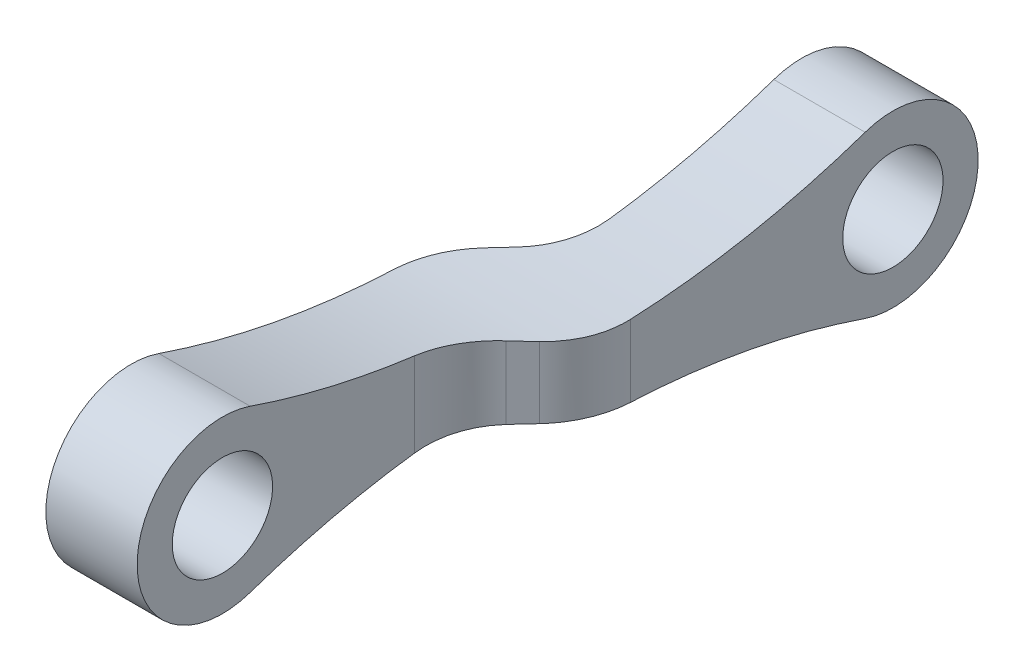
SolidWorks part; units mm, degrees
ref_plane "Front Plane" through (0, 0, 0) normal (0, 0, 1) x (1, 0, 0)
ref_plane "Top Plane" through (0, 0, 0) normal (0, 1, 0) x (1, 0, 0)
ref_plane "Right Plane" through (0, 0, 0) normal (1, 0, 0) x (0, 0, -1)
sketch "Sketch1" plane through (0, 0, 0) normal (1, 0, 0) x (0, 0, -1)
  line L0 (0, 0) -> (-36.65, 0) construction
  line L1 (-39.15, 0) -> (-42.72, 0) construction
  circle A0 centre (0, 0) radius 3.57
  arc A1 (-1.9739, -5.7401) -> (-1.9739, 5.7401) centre (0, 0) ccw
  circle A2 centre (-42.72, 0) radius 3.57
  arc A3 (-40.7461, 5.7401) -> (-40.7461, -5.7401) centre (-42.72, 0) ccw
  arc A4 (-40.7461, 5.7401) -> (-1.9739, 5.7401) centre (-21.36, 62.1155) ccw
  arc A5 (-40.7461, -5.7401) -> (-1.9739, -5.7401) centre (-21.36, -62.1155) cw
  point P13 (-21.36, -2.5)
  dimension "D1" = 7.14
  dimension "D2" = 2.5
  dimension "D4" = 7.14
  dimension "D5" = 2.5
  dimension "D3" = 42.72
  dimension "D6" = 2.5
extrude "Boss-Extrude1" add sketch "Sketch1" along normal blind 11.5
sketch "Sketch2" plane through (0, 0, 0) normal (0, 1, 0) x (1, 0, 0)
  line L0 (5, -48.79) -> (5, -21.3009) construction
  line L1 (0, -48.79) -> (11.5, -48.79) construction
  line L2 (0, -1.9739) -> (0, -40.7461) construction
  line L3 (6.5, -48.79) -> (6.5, -26.36) construction
  line L4 (11.5, 6.07) -> (0, 6.07) construction
  line L5 (11.5, -40.7461) -> (11.5, -1.9739) construction
  line L6 (5, -21.3266) -> (6.5, -21.3343) construction
  line L8 (11.5, -48.79) -> (6.5, -48.79)
  line L9 (11.5, -48.79) -> (11.5, -21.36)
  line L11 (6.5, -48.79) -> (6.5, -26.36)
  line L14 (5, -16.3009) -> (5, 6.07)
  line L15 (5, 6.07) -> (0, 6.07)
  line L16 (0, -21.3009) -> (0, 6.07)
  line L17 (11.5, -21.36) -> (6.5, -26.36)
  line L18 (0, -21.3009) -> (5, -16.3009)
  line L19 (6.5, -21.36) -> (6.5, 6.07) construction
  line L20 (5, -16.3009) -> (5, 6.1882) construction
  dimension "D1" = 5
  dimension "D2" = 5
extrude "Cut-Extrude2" cut sketch "Sketch2" against normal through all and the other way through all
fillet "Fillet1" radius 6.5 4 edges at (0, 0, 21.3009) (5, 0, 16.3009) (6.5, 0, 26.36) (11.5, 0, 21.36)
